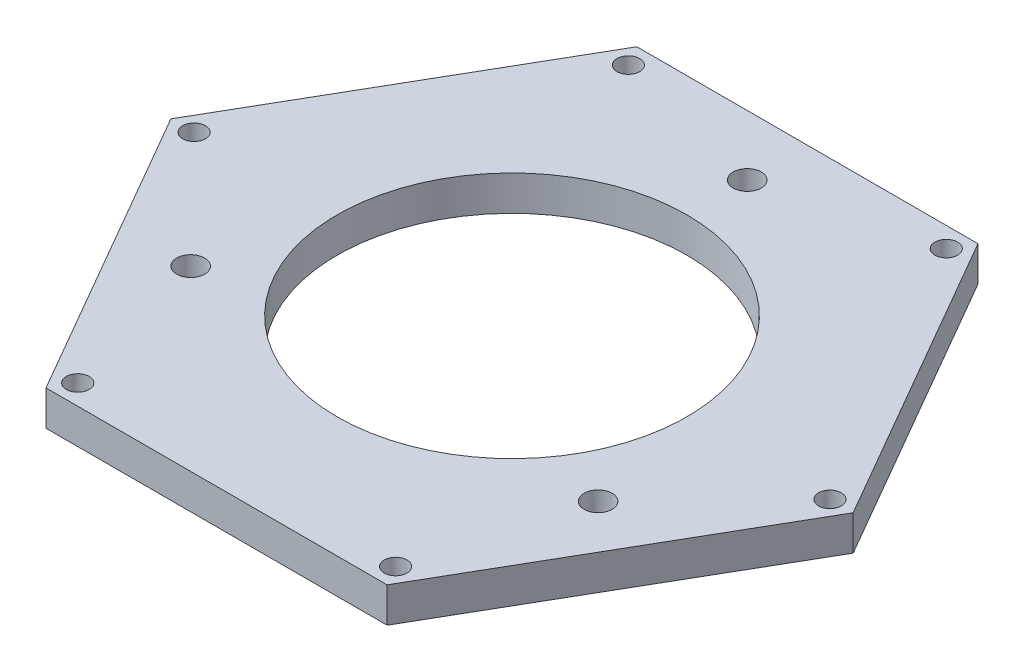
SolidWorks part; units mm, degrees
ref_plane "Front Plane" through (0, 0, 0) normal (0, 0, 1) x (1, 0, 0)
ref_plane "Top Plane" through (0, 0, 0) normal (0, 1, 0) x (1, 0, 0)
ref_plane "Right Plane" through (0, 0, 0) normal (1, 0, 0) x (0, 0, -1)
sketch "Sketch2" plane through (0, 0, 0) normal (0, 1, 0) x (1, 0, 0)
  line L0 (1.5727, 74.4012) -> (-37.4273, 74.4012)
  line L1 (-37.4273, 74.4012) -> (-56.9273, 40.6262)
  line L2 (-56.9273, 40.6262) -> (-37.4273, 6.8512)
  line L3 (-37.4273, 6.8512) -> (1.5727, 6.8512)
  line L4 (1.5727, 6.8512) -> (21.0727, 40.6262)
  line L5 (21.0727, 40.6262) -> (1.5727, 74.4012)
  dimension "D1" = 39
  dimension "D2" = 39
  dimension "D3" = 39
  dimension "D4" = 120
  dimension "D5" = 120
  dimension "D6" = 120
  dimension "D7" = 120
  dimension "D8" = 120
  dimension "D9" = 120
  dimension "D10" = 39
  dimension "D11" = 39
  dimension "D12" = 39
extrude "Boss-Extrude1" add sketch "Sketch2" against normal blind 4
sketch "Sketch3" plane through (0, 0, 0) normal (0, 1, 0) x (1, 0, 0)
  line L0 (1.5727, 74.4012) -> (-37.4273, 74.4012) construction
  line L1 (21.0727, 40.6262) -> (1.5727, 74.4012) construction
  circle A0 centre (-17.9274, 40.6262) radius 20
  dimension "D1" = 33.775
  dimension "D2" = 33.775
extrude "Cut-Extrude1" cut sketch "Sketch3" against normal blind 4
sketch "Sketch4" plane through (0, 0, 0) normal (0, 1, 0) x (1, 0, 0)
  line L0 (1.5727, 6.8512) -> (21.0727, 40.6262) construction
  line L1 (-37.4273, 6.8512) -> (1.5727, 6.8512) construction
  line L2 (-56.9273, 40.6262) -> (-37.4273, 6.8512) construction
  line L3 (11.3227, 23.7387) -> (5.3601, 27.1812) construction
  line L4 (-47.1773, 23.7387) -> (-41.2148, 27.1812) construction
  line L5 (-17.9274, 74.4012) -> (-17.9274, 67.5162) construction
  line L6 (-37.4273, 74.4012) -> (-56.9273, 40.6262) construction
  line L8 (1.5727, 74.4012) -> (-37.4273, 74.4012) construction
  line L9 (21.0727, 40.6262) -> (1.5727, 74.4012) construction
  circle A0 centre (5.3601, 27.1812) radius 1.6
  circle A1 centre (0.2447, 9.1512) radius 1.3
  circle A2 centre (-17.9274, 40.6262) radius 20 construction
  circle A3 centre (-36.0994, 9.1512) radius 1.3
  circle A4 centre (-17.9274, 40.6262) radius 20 construction
  circle A5 centre (-41.2148, 27.1812) radius 1.6
  circle A6 centre (-17.9274, 67.5162) radius 1.6
  circle A7 centre (18.4168, 40.6262) radius 1.3
  circle A8 centre (0.2447, 72.1012) radius 1.3
  circle A9 centre (-54.2715, 40.6262) radius 1.3
  circle A10 centre (-36.0994, 72.1012) radius 1.3
  point P27 (-17.9274, 40.6262)
  point P31 (-36.8864, 9.0083)
  point P36 (-35.8082, 74.4012)
  dimension "D1" = 6.885
  dimension "D2" = 2.3
  dimension "D4" = 3
  dimension "D3" = 2.3
  dimension "D5" = 2.3
  dimension "D6" = 2.3
  dimension "D7" = 2.3
  dimension "D8" = 2.3
  dimension "D9" = 2.3
  dimension "D10" = 2.3
  dimension "D11" = 2.3
  dimension "D12" = 2.3
  dimension "D13" = 2.3
  dimension "D14" = 2.3
extrude "Cut-Extrude2" cut sketch "Sketch4" against normal blind 4
